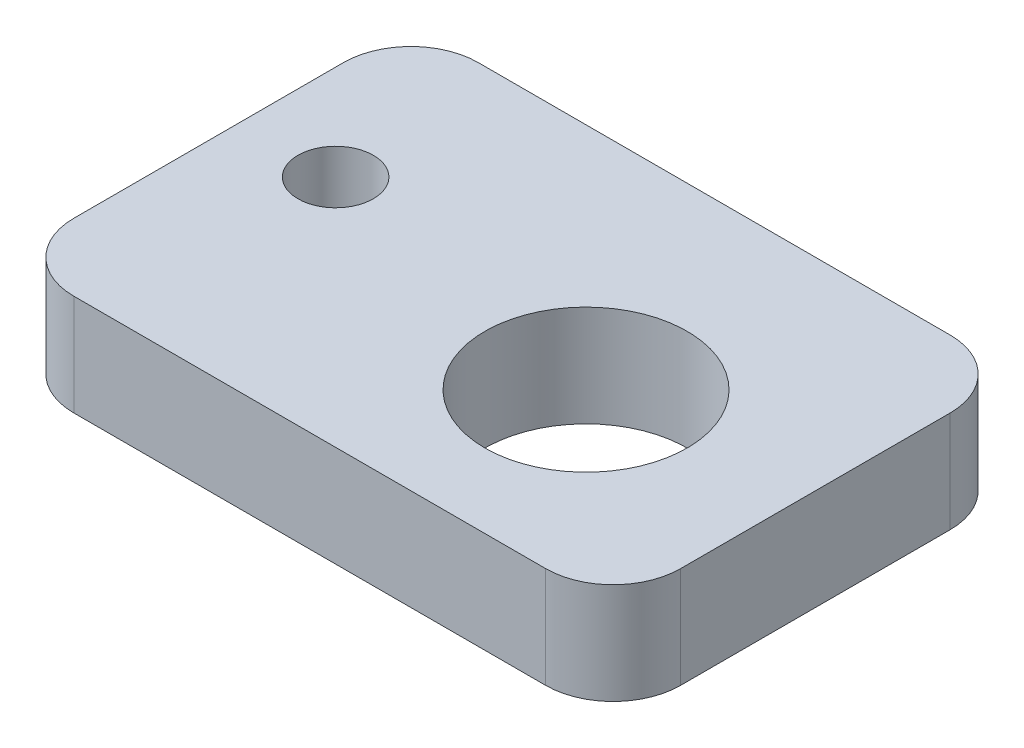
SolidWorks part; units mm, degrees
ref_plane "前视基准面" through (0, 0, 0) normal (0, 0, 1) x (1, 0, 0)
ref_plane "上视基准面" through (0, 0, 0) normal (0, 1, 0) x (1, 0, 0)
ref_plane "右视基准面" through (0, 0, 0) normal (1, 0, 0) x (0, 0, -1)
sketch "草图1" plane through (0, 0, 0) normal (0, 1, 0) x (1, 0, 0)
  line L1 (0, 10.5148) -> (180, 10.5148)
  line L2 (0, 10.5148) -> (0, -109.4852)
  line L3 (0, -109.4852) -> (180, -109.4852)
  line L4 (180, 10.5148) -> (180, -109.4852)
  dimension "D1" = 180
extrude "凸台-拉伸2" add sketch "草图1" along normal blind 30
sketch "草图3" plane through (0, 30, 0) normal (0, 1, 0) x (1, 0, 0)
  line L0 (180, -109.4852) -> (180, 10.5148) construction
  line L1 (0, -109.4852) -> (180, -109.4852) construction
  circle A0 centre (120, -57.5237) radius 30
  circle A1 centre (28.2393, -40.0438) radius 11.186
  point P4 (90, -109.4852)
  dimension "D2" = 60
  dimension "D3" = 60
extrude "切除-拉伸1" cut sketch "草图3" against normal through all
fillet "圆角1" radius 20 4 edges at (0, 15, -10.5148) (180, 15, -10.5148) (180, 15, 109.4852) (0, 15, 109.4852)
shell "抽壳1" thickness 2
